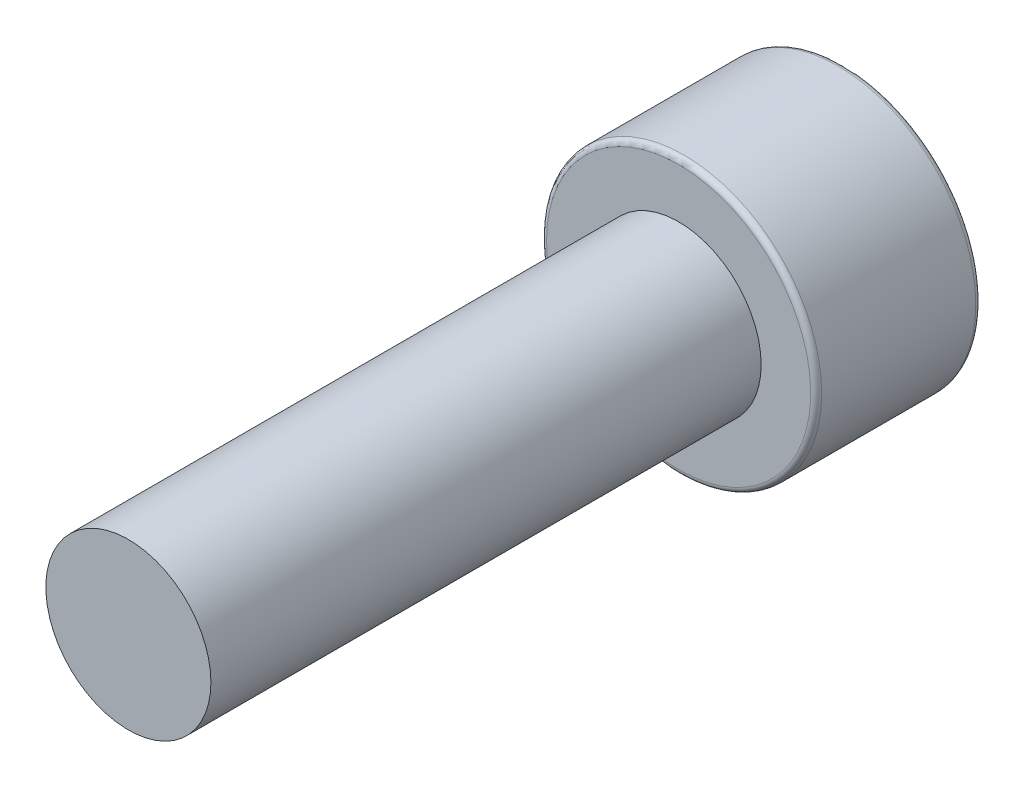
SolidWorks part; units mm, degrees
ref_plane "Alzado" through (0, 0, 0) normal (0, 0, 1) x (1, 0, 0)
ref_plane "Planta" through (0, 0, 0) normal (0, 1, 0) x (1, 0, 0)
ref_plane "Vista lateral" through (0, 0, 0) normal (1, 0, 0) x (0, 0, -1)
sketch "Croquis1" plane through (0, 0, 0) normal (0, 0, 1) x (1, 0, 0)
  circle A1 centre (0, 0) radius 1.5
  dimension "D1" = 3
extrude "Saliente-Extruir1" add sketch "Croquis1" along normal blind 10 contours A1
sketch "Croquis3" plane through (0, 0, 0) normal (0, 0, -1) x (-1, 0, 0)
  circle A0 centre (0, 0) radius 2.5
  dimension "D1" = 5
extrude "Saliente-Extruir3" add sketch "Croquis3" along normal blind 3
sketch "Croquis4" plane through (0, 0, -3) normal (0, 0, -1) x (-1, 0, 0)
  line L1 (1.5, 0) -> (0.75, 1.299)
  line L2 (0.75, 1.299) -> (-0.75, 1.299)
  line L3 (-0.75, 1.299) -> (-1.5, 0)
  line L4 (-1.5, 0) -> (-0.75, -1.299)
  line L5 (-0.75, -1.299) -> (0.75, -1.299)
  line L6 (0.75, -1.299) -> (1.5, 0)
  circle A0 centre (0, 0) radius 1.299 construction
  dimension "D1" = 3
extrude "Cortar-Extruir1" cut sketch "Croquis4" against normal blind 2.5
fillet "Redondeo4" radius 0.1 1 edges at (-2.5, 0, -3)
fillet "Redondeo5" radius 0.1 1 edges at (-2.5, 0, 0)
